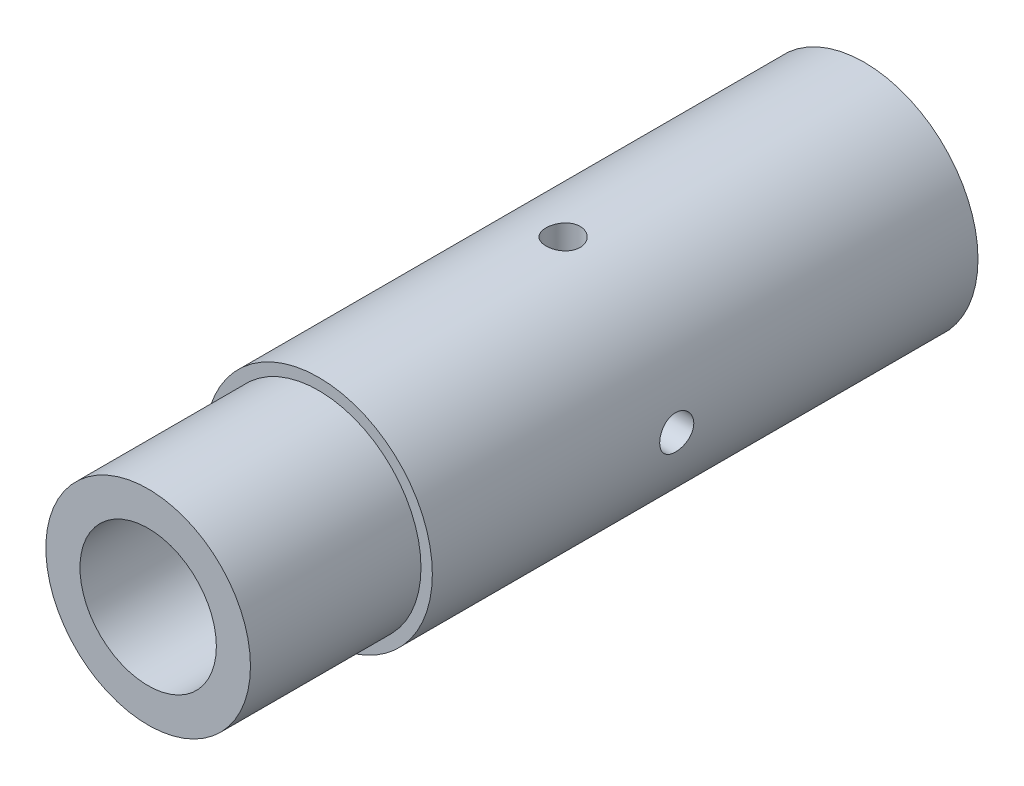
SolidWorks part; units mm, degrees
ref_plane "前视基准面" through (0, 0, 0) normal (0, 0, 1) x (1, 0, 0)
ref_plane "上视基准面" through (0, 0, 0) normal (0, 1, 0) x (1, 0, 0)
ref_plane "右视基准面" through (0, 0, 0) normal (1, 0, 0) x (0, 0, -1)
sketch "草图1" plane through (0, 0, 0) normal (0, 0, 1) x (1, 0, 0)
  circle A0 centre (0, 0) radius 10
  dimension "D1" = 20
extrude "凸台-拉伸1" add sketch "草图1" along normal blind 63
sketch "草图2" plane through (0, 0, 63) normal (0, 0, 1) x (1, 0, 0)
  circle A0 centre (0, 0) radius 9
  dimension "D1" = 18
extrude "切除-拉伸1" cut sketch "草图2" against normal blind 15 flip side to cut
sketch "草图3" plane through (0, 0, 63) normal (0, 0, 1) x (1, 0, 0)
  circle A0 centre (0, 0) radius 6
  dimension "D1" = 12
extrude "切除-拉伸2" cut sketch "草图3" against normal through all
sketch "草图4" plane through (0, 0, 0) normal (1, 0, 0) x (0, 0, -1)
  line L0 (11, 0) -> (-11, 0) construction
  line L1 (0, 11) -> (0, -11) construction
  circle A0 centre (-26.5, 0) radius 1.5
  dimension "D1" = 3
  dimension "D2" = 26.5
extrude "切除-拉伸3" cut sketch "草图4" against normal through all both and the other way through all
pattern_circular "阵列(圆周)1" count 2 over 90 about axis through (0, 0, 63) along (0, 0, 1) of "切除-拉伸3"
